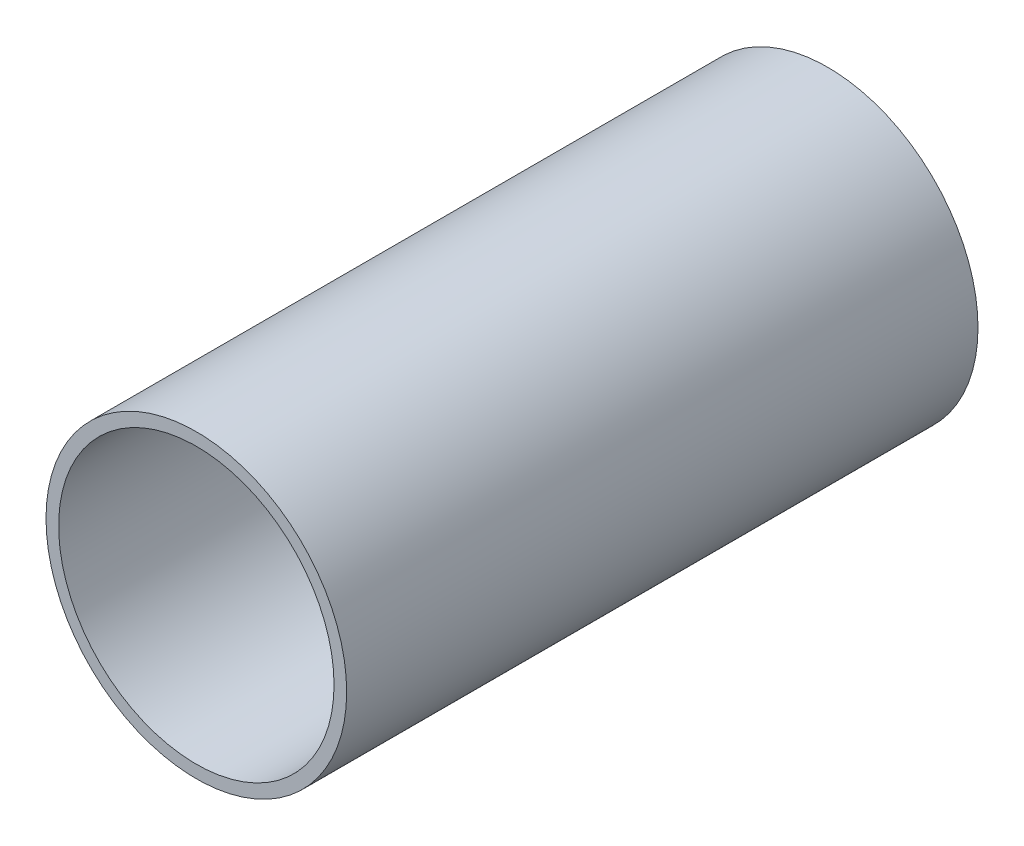
SolidWorks part; units mm, degrees
ref_plane "前基準面" through (0, 0, 0) normal (0, 0, 1) x (1, 0, 0)
ref_plane "上基準面" through (0, 0, 0) normal (0, 1, 0) x (1, 0, 0)
ref_plane "右基準面" through (0, 0, 0) normal (1, 0, 0) x (0, 0, -1)
sketch "草圖1" plane through (0, 0, 0) normal (0, 0, 1) x (1, 0, 0)
  circle A0 centre (0, 0) radius 19.05
  circle A1 centre (0, 0) radius 17.45
  dimension "D1" = 34.9
  dimension "D2" = 38.1
extrude "填料-伸長1" add sketch "草圖1" along normal blind 80
